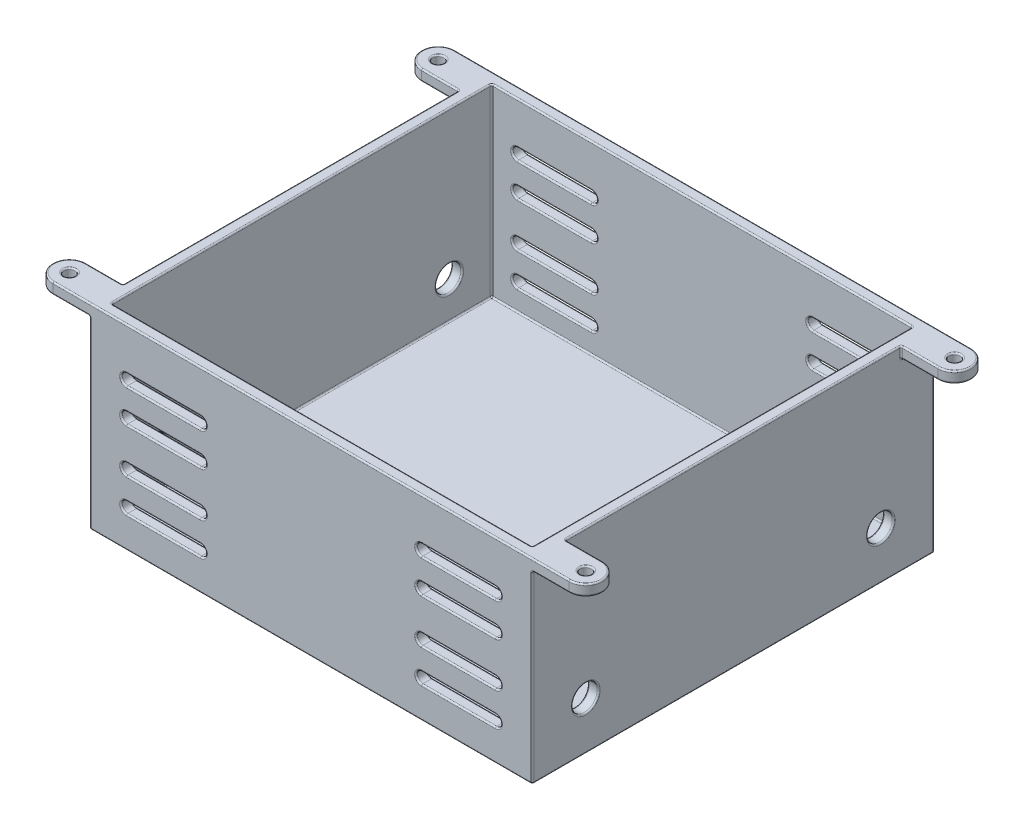
SolidWorks part; units mm, degrees
ref_plane "Front Plane" through (0, 0, 0) normal (0, 0, 1) x (1, 0, 0)
ref_plane "Top Plane" through (0, 0, 0) normal (0, 1, 0) x (1, 0, 0)
ref_plane "Right Plane" through (0, 0, 0) normal (1, 0, 0) x (0, 0, -1)
sketch "Sketch1" plane through (0, 0, 0) normal (0, 1, 0) x (1, 0, 0)
  line L0 (-35, 27.25) -> (35, 27.25) construction
  line L1 (-35, 25) -> (35, 25)
  line L2 (-35, 25) -> (-35, -25)
  line L3 (-35, -25) -> (35, -25)
  line L4 (35, 25) -> (35, -25)
  line L5 (-35, 25) -> (35, -25) construction
  line L6 (-35, -25) -> (35, 25) construction
  line L7 (-30, 27.25) -> (-30, -27.25)
  line L8 (35, -27.25) -> (-35, -27.25) construction
  line L9 (-30, -27.25) -> (30, -27.25)
  line L10 (30, -27.25) -> (30, 27.25)
  line L11 (30, 27.25) -> (-30, 27.25)
  line L12 (-35, 22.75) -> (-30, 22.75)
  line L13 (35, 22.75) -> (30, 22.75)
  line L14 (-35, -22.75) -> (-30, -22.75)
  line L15 (35, -22.75) -> (30, -22.75)
  circle A0 centre (-35, 25) radius 0.75
  circle A1 centre (35, 25) radius 0.75
  circle A2 centre (35, -25) radius 0.75
  circle A3 centre (-35, -25) radius 0.75
  circle A4 centre (-35, 25) radius 2.25
  circle A5 centre (35, 25) radius 2.25
  circle A6 centre (35, -25) radius 2.25
  circle A7 centre (-35, -25) radius 2.25
  point P0 (0, 0)
  point P32 (0, 0)
  point P35 (0, 27.25)
  point P36 (30, 22.75)
  point P37 (30, -22.75)
  point P38 (-30, 22.75)
  dimension "D3" = 1.5
  dimension "D5" = 60
  dimension "D1" = 70
  dimension "D2" = 50
  dimension "D4" = 1.5
sketch "Sketch2" plane through (0, 0, 0) normal (0, 1, 0) x (1, 0, 0)
  line L4 (-30, -27.25) -> (30, -27.25) construction
  line L5 (30, -27.25) -> (30, 27.25) construction
  line L6 (30, 27.25) -> (-30, 27.25) construction
  line L7 (-30, 27.25) -> (-30, -27.25) construction
  line L8 (-28.5, 25.75) -> (-28.5, -25.75)
  line L9 (-28.5, -25.75) -> (28.5, -25.75)
  line L10 (28.5, -25.75) -> (28.5, 25.75)
  line L11 (28.5, 25.75) -> (-28.5, 25.75)
  line L12 (-28.5, 25.75) -> (-28.5, -25.75)
  line L13 (-28.5, -25.75) -> (28.5, -25.75)
  line L14 (28.5, -25.75) -> (28.5, 25.75)
  line L15 (28.5, 25.75) -> (-28.5, 25.75)
  line L16 (-30, -27.25) -> (30, -27.25)
  line L17 (30, -27.25) -> (30, 27.25)
  line L18 (30, 27.25) -> (-30, 27.25)
  line L19 (-30, 27.25) -> (-30, -27.25)
  dimension "D1" = 1.5
extrude "Boss-Extrude1" add sketch "Sketch2" against normal blind 25 contours L12 L13 L14 L15 | L16 L17 L18 L19
sketch "Sketch3" plane through (0, -25, 0) normal (0, -1, 0) x (1, 0, 0)
  line L4 (-30, 27.25) -> (-30, -27.25)
  line L5 (-30, -27.25) -> (30, -27.25)
  line L6 (30, -27.25) -> (30, 27.25)
  line L7 (30, 27.25) -> (-30, 27.25)
  line L8 (-30, 27.25) -> (-30, -27.25)
  line L9 (-30, -27.25) -> (30, -27.25)
  line L10 (30, -27.25) -> (30, 27.25)
  line L11 (30, 27.25) -> (-30, 27.25)
  dimension "D1" = 0
extrude "Boss-Extrude2" add sketch "Sketch3" along normal blind 1.5
sketch "Sketch4" plane through (0, 0, 0) normal (0, 1, 0) x (1, 0, 0)
  line L0 (32.75, 25) -> (30, 25)
  line L1 (34.25, -25) -> (35, -25)
  line L2 (-30, -27.25) -> (-35, -27.25)
  line L3 (35, -22.75) -> (30, -22.75) construction
  line L4 (35, 22.75) -> (30, 22.75) construction
  line L5 (-35, 22.75) -> (-30, 22.75) construction
  line L6 (-35, -22.75) -> (-30, -22.75) construction
  line L7 (35, 25) -> (-35, 25)
  line L8 (35, -25) -> (35, 25)
  line L9 (-35, -25) -> (35, -25)
  line L10 (-35, 25) -> (-35, -25)
  line L11 (35, 25) -> (34.25, 25)
  line L14 (-35, 25) -> (-35, 22.75)
  line L15 (-30, 27.25) -> (-30, -27.25)
  line L16 (-30, -27.25) -> (30, -27.25)
  line L17 (30, -27.25) -> (30, 27.25)
  line L18 (30, 27.25) -> (-30, 27.25)
  line L19 (-30, 27.25) -> (-30, 22.75)
  line L21 (30, -27.25) -> (30, -22.75)
  line L23 (35, -22.75) -> (30, -22.75)
  line L24 (35, 22.75) -> (30, 22.75)
  line L25 (-35, 22.75) -> (-30, 22.75)
  line L26 (-35, -22.75) -> (-30, -22.75)
  line L28 (-35, 27.25) -> (35, 27.25) construction
  line L29 (-35, 27.25) -> (-30, 27.25)
  line L30 (35, 22.75) -> (35, 25)
  line L32 (-30, -22.75) -> (-30, -27.25)
  line L33 (-30, 25) -> (-35, 25)
  line L34 (30, 27.25) -> (35, 27.25)
  line L35 (30, 22.75) -> (30, 27.25)
  line L36 (-30, 27.25) -> (-30, -27.25) construction
  line L37 (35, -27.25) -> (-35, -27.25) construction
  line L38 (30, -27.25) -> (30, 27.25) construction
  line L39 (30, -27.25) -> (30, 27.25)
  line L40 (35, -27.25) -> (30, -27.25)
  line L41 (-30, 27.25) -> (-30, -27.25)
  circle A2 centre (35, -25) radius 2.25
  arc A3 (35, -27.25) -> (35, -22.75) centre (35, -25) ccw
  circle A4 centre (35, 25) radius 2.25
  arc A5 (35, 22.75) -> (35, 27.25) centre (35, 25) ccw
  circle A6 centre (-35, 25) radius 2.25
  arc A7 (-35, 27.25) -> (-35, 22.75) centre (-35, 25) ccw
  circle A8 centre (-35, -25) radius 0.75
  circle A9 centre (-35, -25) radius 0.75
  circle A10 centre (35, -25) radius 0.75
  circle A11 centre (35, -25) radius 0.75
  circle A12 centre (35, 25) radius 0.75
  circle A13 centre (35, 25) radius 0.75
  circle A14 centre (-35, 25) radius 0.75
  circle A15 centre (-35, 25) radius 0.75
  circle A16 centre (-35, -25) radius 2.25
  arc A17 (-35, -22.75) -> (-35, -27.25) centre (-35, -25) ccw
  dimension "D1" = 0
  dimension "D2" = 0
  dimension "D3" = 0
  dimension "D4" = 0
  dimension "D5" = 0
  dimension "D6" = 0
  dimension "D7" = 0
  dimension "D8" = 0
  dimension "D9" = 0
  dimension "D10" = 0
extrude "Boss-Extrude3" add sketch "Sketch4" against normal blind 1.5
sketch "Sketch5" plane through (0, 0, 0) normal (0, 0, 1) x (1, 0, 0)
  line L0 (30, -14) -> (-30, -14) construction
  line L1 (30, -26.5) -> (30, -1.5) construction
  line L2 (-30, -26.5) -> (-30, -1.5) construction
  line L3 (-25, -6.5) -> (-15, -6.5) construction
  line L4 (-25, -5.75) -> (-15, -5.75)
  line L5 (-25, -7.25) -> (-15, -7.25)
  line L6 (-25, -11) -> (-15, -11) construction
  line L7 (-25, -10.25) -> (-15, -10.25)
  line L8 (-25, -11.75) -> (-15, -11.75)
  line L9 (0, -14) -> (0, -20.1846) construction
  line L10 (25, -11) -> (15, -11) construction
  line L11 (25, -10.25) -> (15, -10.25)
  line L12 (25, -11.75) -> (15, -11.75)
  line L13 (25, -6.5) -> (15, -6.5) construction
  line L14 (25, -5.75) -> (15, -5.75)
  line L15 (25, -7.25) -> (15, -7.25)
  line L16 (25, -21.5) -> (15, -21.5) construction
  line L17 (25, -22.25) -> (15, -22.25)
  line L18 (25, -20.75) -> (15, -20.75)
  line L19 (25, -17) -> (15, -17) construction
  line L20 (25, -17.75) -> (15, -17.75)
  line L21 (25, -16.25) -> (15, -16.25)
  line L22 (-25, -17) -> (-15, -17) construction
  line L23 (-25, -17.75) -> (-15, -17.75)
  line L24 (-25, -16.25) -> (-15, -16.25)
  line L25 (-25, -21.5) -> (-15, -21.5) construction
  line L26 (-25, -22.25) -> (-15, -22.25)
  line L27 (-25, -20.75) -> (-15, -20.75)
  arc A0 (-25, -5.75) -> (-25, -7.25) centre (-25, -6.5) ccw
  arc A1 (-15, -7.25) -> (-15, -5.75) centre (-15, -6.5) ccw
  arc A2 (-25, -10.25) -> (-25, -11.75) centre (-25, -11) ccw
  arc A3 (-15, -11.75) -> (-15, -10.25) centre (-15, -11) ccw
  arc A4 (25, -10.25) -> (25, -11.75) centre (25, -11) cw
  arc A5 (15, -11.75) -> (15, -10.25) centre (15, -11) cw
  arc A6 (25, -5.75) -> (25, -7.25) centre (25, -6.5) cw
  arc A7 (15, -7.25) -> (15, -5.75) centre (15, -6.5) cw
  arc A8 (25, -22.25) -> (25, -20.75) centre (25, -21.5) ccw
  arc A9 (15, -20.75) -> (15, -22.25) centre (15, -21.5) ccw
  arc A10 (25, -17.75) -> (25, -16.25) centre (25, -17) ccw
  arc A11 (15, -16.25) -> (15, -17.75) centre (15, -17) ccw
  arc A12 (-25, -17.75) -> (-25, -16.25) centre (-25, -17) cw
  arc A13 (-15, -16.25) -> (-15, -17.75) centre (-15, -17) cw
  arc A14 (-25, -22.25) -> (-25, -20.75) centre (-25, -21.5) cw
  arc A15 (-15, -20.75) -> (-15, -22.25) centre (-15, -21.5) cw
  point P8 (-20, -6.5)
  point P16 (-20, -11)
  point P25 (20, -11)
  point P32 (20, -6.5)
  point P39 (20, -21.5)
  point P46 (20, -17)
  point P53 (-20, -17)
  point P60 (-20, -21.5)
  dimension "D1" = 10
  dimension "D2" = 1.5
  dimension "D3" = 20
  dimension "D4" = 7.5
  dimension "D5" = 4.5
extrude "Cut-Extrude1" cut sketch "Sketch5" against normal through all and the other way through all
sketch "Sketch6" plane through (0, 0, 0) normal (1, 0, 0) x (0, 0, -1)
  line L0 (0, 0) -> (0, -20) construction
  line L1 (-22.75, 0) -> (22.75, 0) construction
  line L2 (0, -20) -> (-20, -20) construction
  circle A0 centre (-20, -20) radius 1.75
  circle A1 centre (20, -20) radius 1.75
  point P4 (20, -20)
  dimension "D1" = 3.5
  dimension "D2" = 20
  dimension "D3" = 20
extrude "Cut-Extrude2" cut sketch "Sketch6" against normal through all and the other way through all
fillet "Fillet1" radius 0.2 196 edges at (-28.5, -20, -18.25) (28.5, -20, -21.75) (-30, -20, -18.25) (30, -20, -21.75) (-28.5, -20, 21.75) (28.5, -20, 18.25) (-30, -20, 21.75) (30, -20, 18.25) (-25.75, -21.5, 27.25) (-20, -22.25, 27.25) (-14.25, -21.5, 27.25) (-20, -20.75, 27.25) (-25.75, -21.5, -27.25) (-20, -22.25, -27.25) (-14.25, -21.5, -27.25) (-20, -20.75, -27.25) (-25.75, -17, 27.25) (-20, -17.75, 27.25) (-14.25, -17, 27.25) (-20, -16.25, 27.25) (-25.75, -17, -27.25) (-20, -17.75, -27.25) (-14.25, -17, -27.25) (-20, -16.25, -27.25) (25.75, -17, 27.25) (20, -16.25, 27.25) (14.25, -17, 27.25) (20, -17.75, 27.25) (25.75, -17, -27.25) (20, -16.25, -27.25) (14.25, -17, -27.25) (20, -17.75, -27.25) (25.75, -21.5, 27.25) (20, -20.75, 27.25) (14.25, -21.5, 27.25) (20, -22.25, 27.25) (25.75, -21.5, -27.25) (20, -20.75, -27.25) (14.25, -21.5, -27.25) (20, -22.25, -27.25) (25.75, -6.5, 27.25) (20, -5.75, 27.25) (14.25, -6.5, 27.25) (20, -7.25, 27.25) (25.75, -6.5, -27.25) (20, -5.75, -27.25) (14.25, -6.5, -27.25) (20, -7.25, -27.25) (25.75, -11, 27.25) (20, -10.25, 27.25) (14.25, -11, 27.25) (20, -11.75, 27.25) (25.75, -11, -27.25) (20, -10.25, -27.25) (14.25, -11, -27.25) (20, -11.75, -27.25) (-25.75, -11, 27.25) (-20, -11.75, 27.25) (-14.25, -11, 27.25) (-20, -10.25, 27.25) (-25.75, -11, -27.25) (-20, -11.75, -27.25) (-14.25, -11, -27.25) (-20, -10.25, -27.25) (-25.75, -6.5, 27.25) (-20, -7.25, 27.25) (-14.25, -6.5, 27.25) (-20, -5.75, 27.25) (-25.75, -6.5, -27.25) (-20, -7.25, -27.25) (-14.25, -6.5, -27.25) (-20, -5.75, -27.25) (-20, -7.25, -25.75) (-14.25, -6.5, -25.75) (-20, -5.75, -25.75) (-25.75, -6.5, -25.75) (-20, -22.25, -25.75) (-14.25, -21.5, -25.75) (-20, -20.75, -25.75) (-25.75, -21.5, -25.75) (-20, -17.75, -25.75) (-14.25, -17, -25.75) (-20, -16.25, -25.75) (-25.75, -17, -25.75) (20, -16.25, -25.75) (14.25, -17, -25.75) (20, -17.75, -25.75) (25.75, -17, -25.75) (-20, -11.75, -25.75) (-14.25, -11, -25.75) (-20, -10.25, -25.75) (-25.75, -11, -25.75) (20, -10.25, -25.75) (14.25, -11, -25.75) (20, -11.75, -25.75) (25.75, -11, -25.75) (20, -5.75, -25.75) (14.25, -6.5, -25.75) (20, -7.25, -25.75) (25.75, -6.5, -25.75) (20, -20.75, -25.75) (14.25, -21.5, -25.75) (20, -22.25, -25.75) (25.75, -21.5, -25.75) (35, -1.5, -24.25) (35, 0, -24.25) (32.5, 0, -22.75) (32.5, -1.5, -22.75) (37.25, 0, -25) (37.25, -1.5, -25) (30, -1.5, -25) (32.5, -1.5, -27.25) (30, -0.75, -22.75) (35, -1.5, 25.75) (35, 0, 25.75) (37.25, 0, 25) (37.25, -1.5, 25) (32.5, 0, 22.75) (32.5, -1.5, 22.75) (32.5, -1.5, 27.25) (30, -1.5, 25) (30, -0.75, 22.75) (-35, -1.5, 25.75) (-35, 0, 25.75) (-32.5, 0, 22.75) (-32.5, -1.5, 22.75) (-37.25, 0, 25) (-37.25, -1.5, 25) (-32.5, -1.5, 27.25) (-30, -1.5, 25) (-30, -0.75, 22.75) (-37.25, 0, -25) (-37.25, -1.5, -25) (-32.5, 0, -22.75) (-32.5, -1.5, -22.75) (-35, -1.5, -24.25) (-35, 0, -24.25) (-30, -1.5, -25) (-32.5, -1.5, -27.25) (-30, -0.75, -22.75) (0, -26.5, 27.25) (-30, -26.5, 0) (0, -26.5, -27.25) (30, -26.5, 0) (0, 0, -25.75) (0, -25, -25.75) (-28.5, 0, 0) (-28.5, -25, 0) (0, 0, 25.75) (0, -25, 25.75) (28.5, 0, 0) (28.5, -25, 0) (-28.5, -12.5, -25.75) (-28.5, -12.5, 25.75) (28.5, -12.5, 25.75) (28.5, -12.5, -25.75) (-30, 0, 0) (0, 0, 27.25) (30, 0, 0) (0, 0, -27.25) (-30, -14, 27.25) (30, -14, -27.25) (-30, -14, -27.25) (-20, -7.25, 25.75) (-14.25, -6.5, 25.75) (-20, -5.75, 25.75) (-25.75, -6.5, 25.75) (-20, -22.25, 25.75) (-14.25, -21.5, 25.75) (-20, -20.75, 25.75) (-25.75, -21.5, 25.75) (-20, -17.75, 25.75) (-14.25, -17, 25.75) (-20, -16.25, 25.75) (-25.75, -17, 25.75) (20, -16.25, 25.75) (14.25, -17, 25.75) (20, -17.75, 25.75) (25.75, -17, 25.75) (-20, -11.75, 25.75) (-14.25, -11, 25.75) (-20, -10.25, 25.75) (-25.75, -11, 25.75) (20, -10.25, 25.75) (14.25, -11, 25.75) (20, -11.75, 25.75) (25.75, -11, 25.75) (20, -5.75, 25.75) (14.25, -6.5, 25.75) (20, -7.25, 25.75) (25.75, -6.5, 25.75) (20, -20.75, 25.75) (14.25, -21.5, 25.75) (20, -22.25, 25.75) (25.75, -21.5, 25.75) (30, -14, 27.25)
